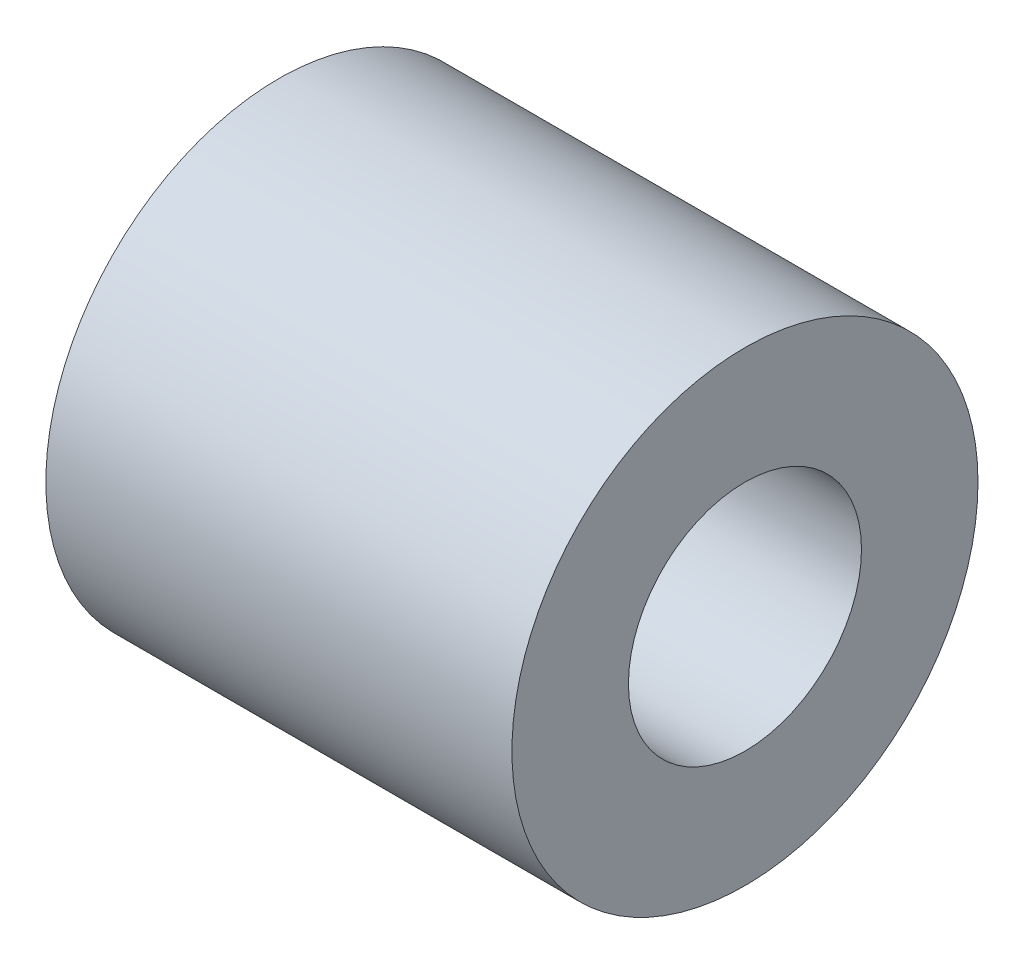
SolidWorks part; units mm, degrees
material "AISI 4130 Steel, normalized at 870C"
ref_plane "Front Plane" through (0, 0, 0) normal (0, 0, 1) x (1, 0, 0)
ref_plane "Top Plane" through (0, 0, 0) normal (0, 1, 0) x (1, 0, 0)
ref_plane "Right Plane" through (0, 0, 0) normal (1, 0, 0) x (0, 0, -1)
sketch "Sketch1" plane through (0, 0, 0) normal (1, 0, 0) x (0, 0, -1)
  circle A0 centre (0, 0) radius 10
extrude "Boss-Extrude1" add sketch "Sketch1" along normal blind 2
sketch "Sketch2" plane through (2, 0, 0) normal (1, 0, 0) x (0, 0, -1)
  circle A0 centre (0, 0) radius 5
  circle A1 centre (0, 0) radius 10
extrude "Boss-Extrude2" add sketch "Sketch2" along normal blind 18
